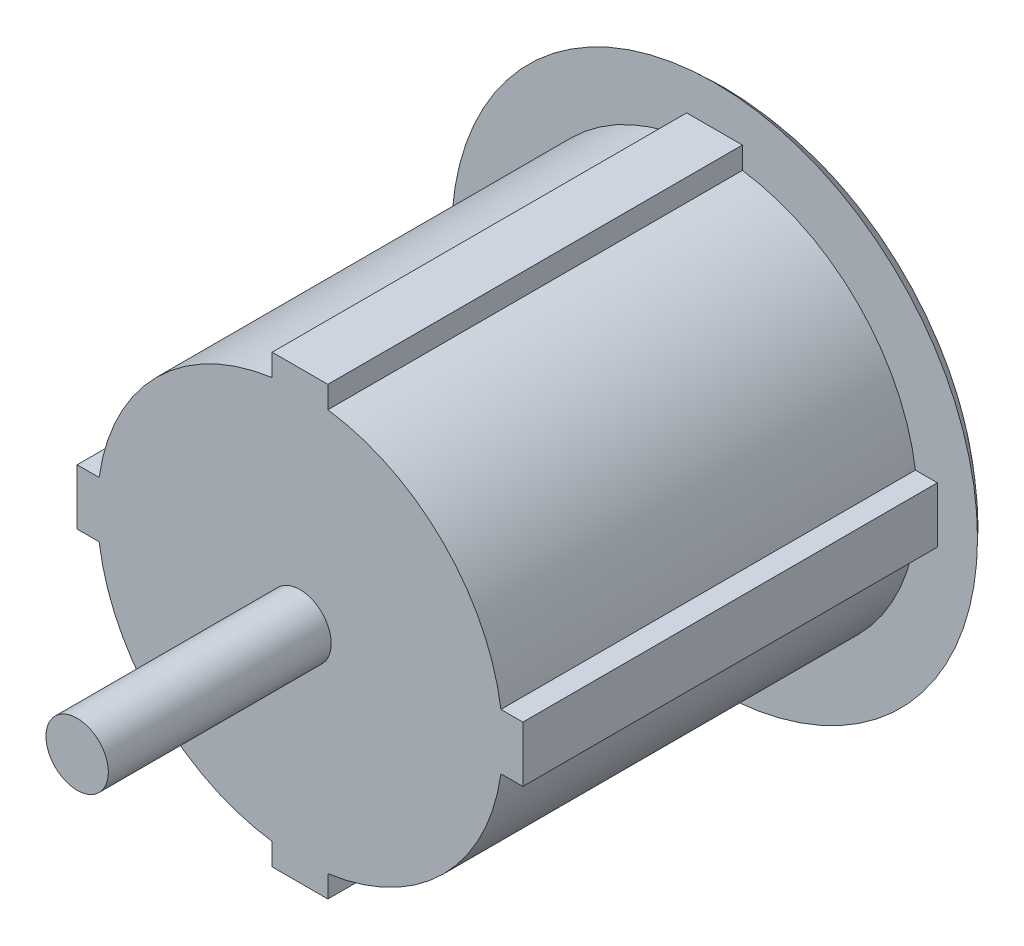
SolidWorks part; units mm, degrees
ref_plane "前视基准面" through (0, 0, 0) normal (0, 0, 1) x (1, 0, 0)
ref_plane "上视基准面" through (0, 0, 0) normal (0, 1, 0) x (1, 0, 0)
ref_plane "右视基准面" through (0, 0, 0) normal (1, 0, 0) x (0, 0, -1)
sketch "草图1" plane through (0, 0, 0) normal (0, 0, 1) x (1, 0, 0)
  circle A0 centre (0, 0) radius 9.1
  dimension "D1" = 18.2
extrude "凸台-拉伸1" add sketch "草图1" along normal blind 20.4
sketch "草图2" plane through (0, 0, 0) normal (1, 0, 0) x (0, 0, -1)
  line L0 (-1.8, 9.1) -> (-1.8, 11.8)
  line L1 (0, 9.1) -> (-20.4, 9.1) construction
  line L2 (-1.8, 9.1) -> (0, 9.1)
  arc A0 (0, 9.1) -> (-1.8, 11.8) centre (-5.7063, 7.2458) ccw
  dimension "D2" = 6
  dimension "D1" = 2.7
  dimension "D3" = 1.8
ref_axis "基准轴1" through (0, 0, 20.4) along (0, 0, -1)
revolve "旋转1" add sketch "草图2" angle 360 about axis through (0, 0, 20.4) along (0, 0, -1)
sketch "草图3" plane through (0, 0, 0) normal (0, 0, -1) x (-1, 0, 0)
  circle A0 centre (0, 0) radius 8.2947
  circle A1 centre (0, 0) radius 7.2947
  dimension "D1" = 1
extrude "切除-拉伸1" cut sketch "草图3" against normal blind 0.5
sketch "草图4" plane through (0, 0, 20.4) normal (0, 0, 1) x (1, 0, 0)
  line L0 (0, 0) -> (0, 17.7179) construction
  line L2 (-1.25, 10) -> (1.25, 10)
  line L3 (-1.25, 10) -> (-1.25, 8)
  line L4 (-1.25, 8) -> (1.25, 8)
  line L5 (1.25, 10) -> (1.25, 8)
  line L6 (-1.25, 10) -> (1.25, 8) construction
  line L7 (-1.25, 8) -> (1.25, 10) construction
  point P2 (0, 9)
  dimension "D1" = 10
  dimension "D2" = 8
  dimension "D3" = 2.5
extrude "凸台-拉伸2" add sketch "草图4" against normal up to surface (18.6 mm away) up to face at (-9.1, 0, 1.8)
pattern_circular "阵列(圆周)1" count 4 over 360 about axis through (0, 0, 0) along (0, 0, 1) of "凸台-拉伸2"
sketch "草图5" plane through (0, 0, 20.4) normal (0, 0, 1) x (1, 0, 0)
  circle A0 centre (0, 0) radius 1.4
  dimension "D1" = 2.8
extrude "凸台-拉伸3" add sketch "草图5" along normal blind 10
